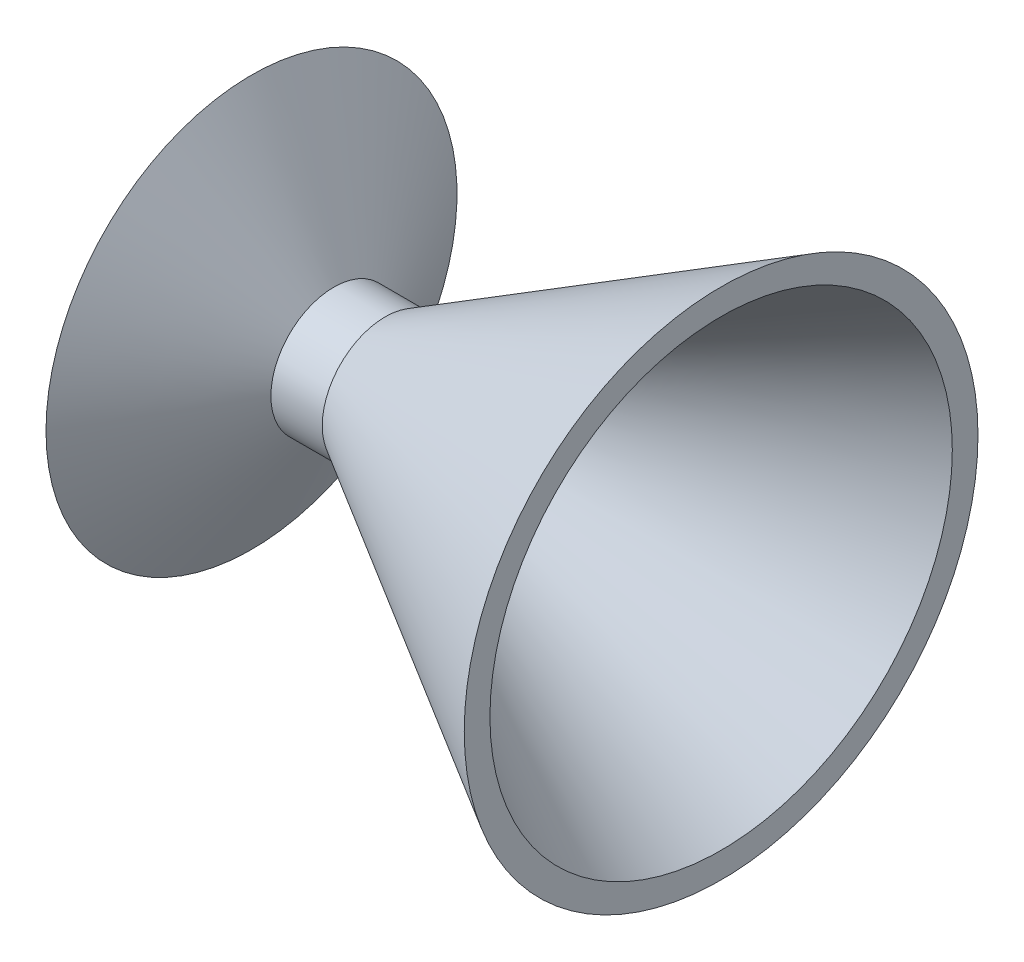
SolidWorks part; units mm, degrees
material "C (Graphite)"
ref_plane "Front Plane" through (0, 0, 0) normal (0, 0, 1) x (1, 0, 0)
ref_plane "Top Plane" through (0, 0, 0) normal (0, 1, 0) x (1, 0, 0)
ref_plane "Right Plane" through (0, 0, 0) normal (1, 0, 0) x (0, 0, -1)
sketch "Sketch1" plane through (0, 0, 0) normal (0, 0, 1) x (1, 0, 0)
  line L0 (0, 0) -> (215.3765, 0) construction
  line L1 (0, 0) -> (0, 93.6004) construction
  line L2 (0, 15.5575) -> (83.0388, 63.5)
  line L3 (0, 7.9375) -> (83.0388, 57.15)
  line L4 (83.0388, 63.5) -> (83.0388, 57.15)
  line L9 (0, 15.5575) -> (-12.7, 15.5575)
  line L10 (0, 7.9375) -> (-12.7, 7.9375)
  line L14 (-12.7, 15.5575) -> (-33.0473, 50.8)
  line L22 (-12.7, 7.9375) -> (-33.0473, 41.275)
  line L23 (-33.0473, 50.8) -> (-33.0473, 41.275)
  point P8 (-33.0473, 48.7164)
  point P11 (-33.2665, 51.2075)
  point P14 (-20.7368, 45.7458)
  dimension "D1" = 6.35
  dimension "D2" = 7.62
  dimension "D3" = 7.9375
  dimension "D4" = 9.525
  dimension "D5" = 12.7
  dimension "D6" = 63.5
  dimension "D7" = 12.7
  dimension "D8" = 30
  dimension "D9" = 60
  dimension "D10" = 50.8
revolve "Revolve1" add sketch "Sketch1" angle 360 about L0
